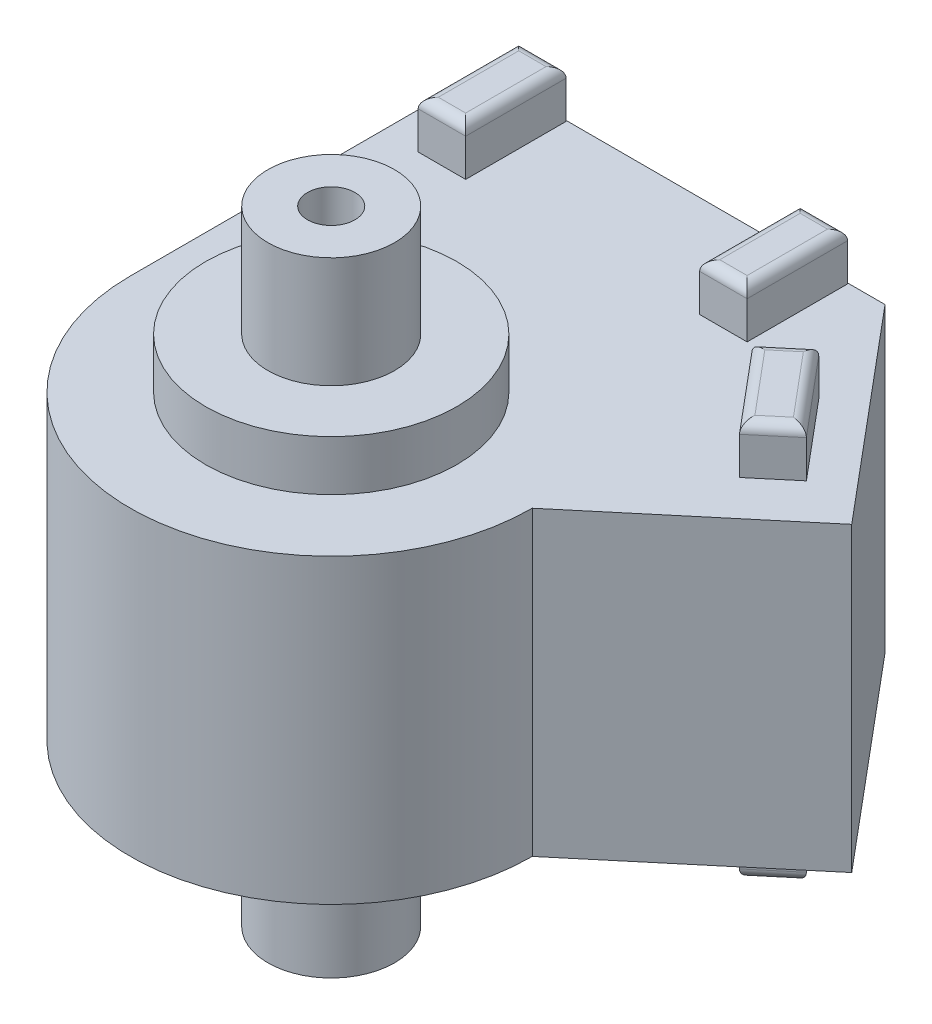
SolidWorks part; units mm, degrees
ref_plane "Front Plane" through (0, 0, 0) normal (0, 0, 1) x (1, 0, 0)
ref_plane "Top Plane" through (0, 0, 0) normal (0, 1, 0) x (1, 0, 0)
ref_plane "Right Plane" through (0, 0, 0) normal (1, 0, 0) x (0, 0, -1)
sketch "Sketch1" plane through (0, 0, 0) normal (0, 0, 1) x (1, 0, 0)
  line L0 (-12.7, -9.525) -> (-12.7, 9.525)
  line L1 (-12.7, 9.525) -> (-7.9375, 9.525)
  line L2 (-7.9375, 9.525) -> (-7.9375, 12.7)
  line L3 (-7.9375, 12.7) -> (-4, 12.7)
  line L4 (-4, 12.7) -> (-4, 19.7)
  line L5 (0, 0) -> (0, 19.7) construction
  line L6 (0, 19.7) -> (-4, 19.7)
  line L7 (0, 0) -> (-12.7, 0) construction
  line L8 (-4, 19.7) -> (4, 19.7) construction
  line L9 (-7.9375, 12.7) -> (7.9375, 12.7) construction
  line L10 (-12.7, 9.525) -> (12.7, 9.525) construction
  line L11 (-12.7, -9.525) -> (-7.9375, -9.525)
  line L12 (-7.9375, -9.525) -> (-7.9375, -12.7)
  line L13 (-7.9375, -12.7) -> (-4, -12.7)
  line L14 (-4, -12.7) -> (-4, -19.7)
  line L15 (-4, -19.7) -> (0, -19.7)
  line L16 (0, -19.7) -> (0, 19.7)
  point P9 (0, 9.525)
  point P12 (0, 19.7)
  point P14 (0, 12.7)
  dimension "D1" = 19.05
  dimension "D2" = 3.175
  dimension "D3" = 7
  dimension "D4" = 8
  dimension "D5" = 15.875
  dimension "D6" = 25.4
  dimension "D7" = 25.4
revolve "Revolve1" add sketch "Sketch1" angle 360 about L5
sketch "Sketch2" plane through (0, 9.525, 0) normal (0, 1, 0) x (1, 0, 0)
  line L0 (12.7, 0) -> (23.6726, 9.2071)
  line L1 (23.6726, 9.2071) -> (12.7, 22.2837)
  line L3 (12.7, 22.2837) -> (-12.7, 22.2837)
  line L4 (-12.7, 22.2837) -> (-12.7, 0)
  line L5 (-12.7, 0) -> (12.7, 0)
  line L6 (12.7, 0) -> (12.7, 22.2837) construction
  circle A0 centre (0, 0) radius 12.7 construction
  dimension "D1" = 50
  dimension "D2" = 25.4
extrude "Boss-Extrude1" add sketch "Sketch2" against normal up to surface (19.05 mm away) up to face at (7.9375, -9.525, 0)
sketch "Sketch3" plane through (0, 19.7, 0) normal (0, 1, 0) x (1, 0, 0)
  circle A0 centre (0, 0) radius 1.4986
  dimension "D1" = 2.9972
extrude "Cut-Extrude1" cut sketch "Sketch3" against normal through all
sketch "Sketch4" plane through (0, 9.525, 0) normal (0, 1, 0) x (1, 0, 0)
  line L5 (15.7794, 15.0179) -> (13.4834, 13.0913)
  line L6 (13.4834, 13.0913) -> (17.5651, 8.227)
  line L7 (17.5651, 8.227) -> (19.8611, 10.1535)
  line L8 (19.8611, 10.1535) -> (15.7794, 15.0179)
  line L9 (12.7, 0) -> (23.6726, 9.2071) construction
  line L10 (23.6726, 9.2071) -> (12.7, 22.2837) construction
  dimension "D1" = 2.9972
  dimension "D2" = 6.35
  dimension "D3" = 3.175
  dimension "D4" = 2.3114
extrude "Boss-Extrude2" add sketch "Sketch4" along normal blind 2.9972
sketch "Sketch5" plane through (0, 9.525, 0) normal (0, 1, 0) x (1, 0, 0)
  line L0 (-12.7, 22.2837) -> (-12.7, 0) construction
  line L1 (-10.3886, 22.2329) -> (-7.3914, 22.2329)
  line L2 (-10.3886, 22.2329) -> (-10.3886, 15.8829)
  line L3 (-10.3886, 15.8829) -> (-7.3914, 15.8829)
  line L4 (-7.3914, 22.2329) -> (-7.3914, 15.8829)
  line L5 (-10.3886, 22.2329) -> (-7.3914, 15.8829) construction
  line L6 (-10.3886, 15.8829) -> (-7.3914, 22.2329) construction
  line L7 (7.3914, 22.2329) -> (10.3886, 22.2329)
  line L8 (7.3914, 22.2329) -> (7.3914, 15.8829)
  line L9 (7.3914, 15.8829) -> (10.3886, 15.8829)
  line L10 (10.3886, 22.2329) -> (10.3886, 15.8829)
  line L11 (7.3914, 22.2329) -> (10.3886, 15.8829) construction
  line L12 (7.3914, 15.8829) -> (10.3886, 22.2329) construction
  line L13 (12.7, 22.2837) -> (-12.7, 22.2837) construction
  point P0 (-8.89, 19.0579)
  point P5 (8.89, 19.0579)
  dimension "D1" = 2.9972
  dimension "D2" = 2.9972
  dimension "D3" = 6.35
  dimension "D4" = 2.3114
  dimension "D5" = 17.78
  dimension "D6" = 0.0508
extrude "Boss-Extrude3" add sketch "Sketch5" along normal blind 2.9972
fillet "Fillet1" radius 0.635 12 edges at (18.7131, 12.5222, -9.1902) (15.5242, 12.5222, -10.6591) (14.6314, 12.5222, -14.0546) (17.8202, 12.5222, -12.5857) (8.89, 12.5222, -15.8829) (7.3914, 12.5222, -19.0579) (8.89, 12.5222, -22.2329) (10.3886, 12.5222, -19.0579) (-8.89, 12.5222, -15.8829) (-10.3886, 12.5222, -19.0579) (-8.89, 12.5222, -22.2329) (-7.3914, 12.5222, -19.0579)
ref_plane "Plane1" through (0, 0, 0) normal (0, 1, 0) x (1, 0, 0)
mirror "Mirror1" about plane through (0, 0, 0) normal (0, 1, 0) of "Fillet1", "Boss-Extrude3", "Boss-Extrude2"
